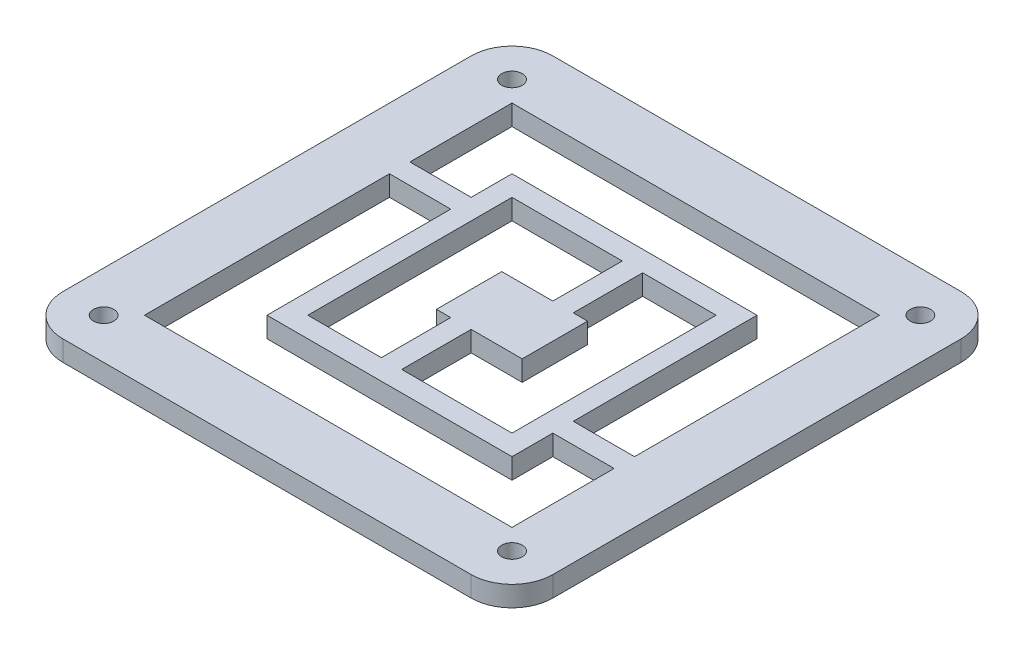
SolidWorks part; units mm, degrees
ref_plane "Front Plane" through (0, 0, 0) normal (0, 0, 1) x (1, 0, 0)
ref_plane "Top Plane" through (0, 0, 0) normal (0, 1, 0) x (1, 0, 0)
ref_plane "Right Plane" through (0, 0, 0) normal (1, 0, 0) x (0, 0, -1)
sketch "Sketch1" plane through (0, 0, 0) normal (0, 1, 0) x (1, 0, 0)
  line L0 (-50, 50) -> (50, -50) construction
  line L1 (-50, -50) -> (50, 50) construction
  line L3 (-50, -60) -> (50, -60)
  line L4 (-60, -50) -> (-60, 50)
  line L5 (-50, 60) -> (50, 60)
  line L8 (60, -50) -> (60, 50)
  line L9 (-60, -60) -> (60, 60) construction
  line L10 (-60, 60) -> (60, -60) construction
  line L11 (-25, -25) -> (-25, 25)
  line L16 (-43.3599, -43.3599) -> (43.3599, 43.3599) construction
  line L17 (-43.3599, 43.3599) -> (43.3599, -43.3599) construction
  line L18 (-45, -45) -> (45, -45)
  line L19 (-45, -45) -> (-45, 45)
  line L20 (-45, 45) -> (45, 45)
  line L21 (45, -45) -> (45, 45)
  line L22 (-45, -45) -> (45, 45) construction
  line L23 (-45, 45) -> (45, -45) construction
  line L24 (-30, -30) -> (30, -30)
  line L25 (-30, -30) -> (-30, 30)
  line L26 (-30, 30) -> (30, 30)
  line L27 (30, -30) -> (30, 30)
  line L28 (-30, -30) -> (30, 30) construction
  line L29 (-30, 30) -> (30, -30) construction
  line L30 (-25, 25) -> (25, 25)
  line L31 (25, -25) -> (25, 25)
  line L32 (-25, -25) -> (25, -25)
  line L34 (-10.5, 8) -> (10.5, 8)
  line L35 (-10.5, 8) -> (-10.5, -8)
  line L36 (-10.5, -8) -> (10.5, -8)
  line L37 (10.5, 8) -> (10.5, -8)
  line L38 (-10.5, 8) -> (10.5, -8) construction
  line L39 (-10.5, -8) -> (10.5, 8) construction
  circle A0 centre (-50, 50) radius 2.5
  circle A1 centre (50, 50) radius 2.5
  circle A2 centre (50, -50) radius 2.5
  circle A3 centre (-50, -50) radius 2.5
  arc A4 (60, 50) -> (50, 60) centre (50, 50) ccw
  arc A5 (50, -60) -> (60, -50) centre (50, -50) ccw
  arc A6 (-50, -60) -> (-60, -50) centre (-50, -50) cw
  arc A7 (-60, 50) -> (-50, 60) centre (-50, 50) cw
  point P8 (0, 0)
  point P9 (0, 0)
  point P27 (0, 0)
  point P32 (0, 0)
  point P37 (0, 0)
  point P46 (0, 0)
  dimension "D1" = 5
  dimension "D6" = 10
  dimension "D2" = 100
  dimension "D3" = 100
  dimension "D4" = 120
  dimension "D5" = 120
  dimension "D7" = 90
  dimension "D8" = 90
  dimension "D9" = 60
  dimension "D10" = 60
  dimension "D12" = 16
  dimension "D13" = 21
  dimension "D11" = 5
extrude "Boss-Extrude1" add sketch "Sketch1" along normal blind 5 contours A7 L4 A6 L3 A5 L8 A4 L5 A3 A2 A1 A0 L21 L18 L19 L20 | L24 L27 L26 L25 L32 L11 L30 L31 | L37 L34 L35 L36
sketch "Sketch2" plane through (0, 0, 0) normal (0, 1, 0) x (1, 0, 0)
  line L0 (-10.5, -8) -> (10.5, -8) construction
  line L1 (-7, -8) -> (-2, -8)
  line L2 (-7, -8) -> (-7, -25)
  line L3 (-7, -25) -> (-2, -25)
  line L4 (-2, -8) -> (-2, -25)
  line L5 (-25, -25) -> (25, -25) construction
  line L6 (-10.5, 8) -> (10.5, 8) construction
  line L7 (2, 8) -> (7, 8)
  line L8 (2, 8) -> (2, 25)
  line L9 (2, 25) -> (7, 25)
  line L10 (7, 8) -> (7, 25)
  line L11 (-25, 25) -> (25, 25) construction
  line L12 (-30, -30) -> (-30, 30) construction
  line L13 (-30, 20) -> (-45, 20)
  line L14 (-30, 20) -> (-30, 15)
  line L15 (-30, 15) -> (-45, 15)
  line L16 (-45, 20) -> (-45, 15)
  line L17 (-45, -45) -> (-45, 45) construction
  line L18 (30, -30) -> (30, 30) construction
  line L19 (30, -20) -> (45, -20)
  line L20 (30, -20) -> (30, -15)
  line L21 (30, -15) -> (45, -15)
  line L22 (45, -20) -> (45, -15)
  line L23 (45, -45) -> (45, 45) construction
  dimension "D1" = 5
  dimension "D2" = 5
  dimension "D3" = 5
  dimension "D4" = 5
  dimension "D5" = 25
  dimension "D6" = 25
  dimension "D7" = 18
  dimension "D8" = 18
extrude "Boss-Extrude2" add sketch "Sketch2" along normal blind 5
